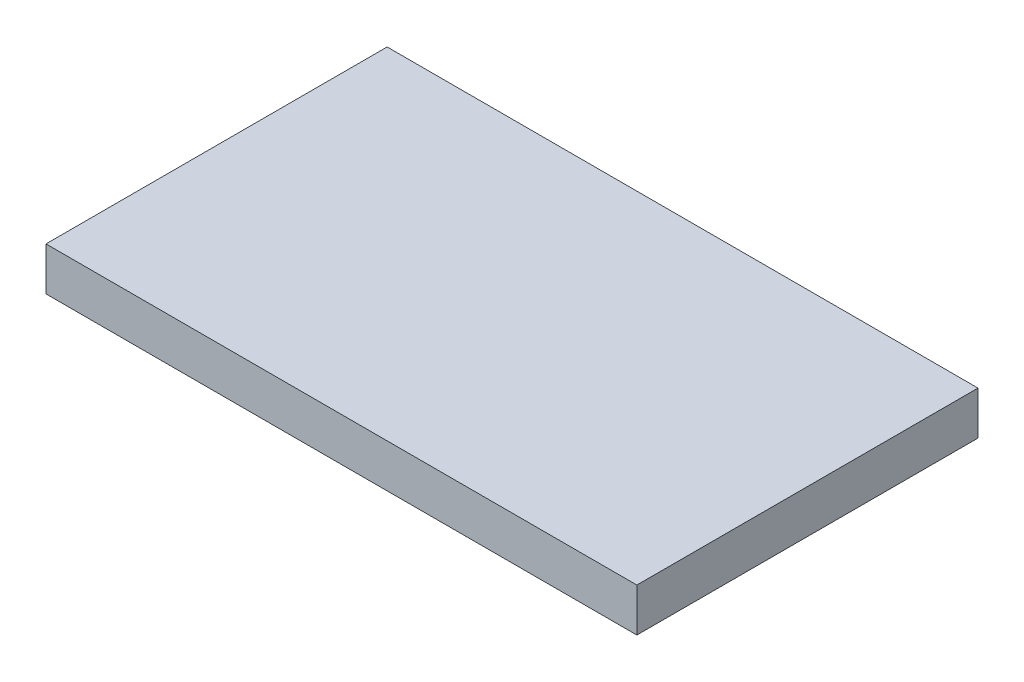
SolidWorks part; units mm, degrees
ref_plane "Plan de face" through (0, 0, 0) normal (0, 0, 1) x (1, 0, 0)
ref_plane "Plan de dessus" through (0, 0, 0) normal (0, 1, 0) x (1, 0, 0)
ref_plane "Plan de droite" through (0, 0, 0) normal (1, 0, 0) x (0, 0, -1)
sketch "Esquisse2" plane through (0, 0, 0) normal (0, 1, 0) x (1, 0, 0)
  line L0 (-43.3013, 0) -> (43.3013, 0) construction
  line L1 (-43.3013, 25) -> (43.3013, 25)
  line L2 (-43.3013, 25) -> (-43.3013, -25)
  line L3 (-43.3013, -25) -> (43.3013, -25)
  line L4 (43.3013, 25) -> (43.3013, -25)
  line L5 (0, 100) -> (-43.3013, 25) construction
  line L6 (0, 100) -> (43.3013, 25) construction
  line L7 (0, 100) -> (0, 0) construction
  circle A0 centre (0, 100) radius 75 construction
  point P8 (0, 0)
  dimension "D2" = 150
  dimension "D1" = 50
  dimension "D3" = 60
extrude "Boss.-Extru.1" add sketch "Esquisse2" along normal blind 6.35
